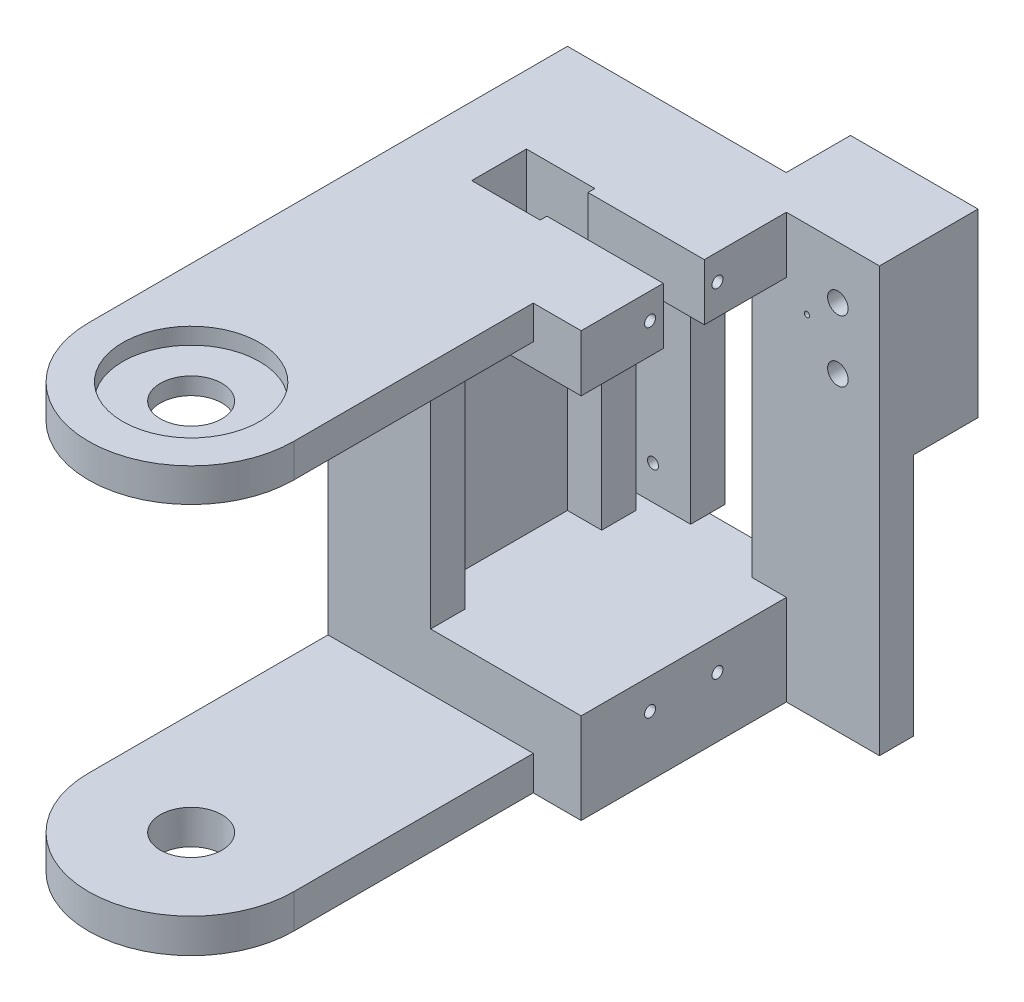
SolidWorks part; units mm, degrees
other "Marquage1"
sketch "Esquisse9" plane through (30.25, -27, 30) normal (0.9363, -0.2766, 0.2166) x (0.221, -0.0157, -0.9752)
sketch "Esquisse35" plane through (11.75, 27, 30) normal (0.9363, -0.2766, 0.2166) x (0.221, -0.0157, -0.9752)
sketch "Esquisse43" plane through (11.75, 27, 30) normal (0.9363, -0.2766, 0.2166) x (0.221, -0.0157, -0.9752)
sketch "Esquisse62" plane through (26.35, 27, 80) normal (0.9363, -0.2766, 0.2166) x (0.221, -0.0157, -0.9752)
ref_plane "Plan de face" through (0, 0, 0) normal (0, 0, 1) x (1, 0, 0)
ref_plane "Plan de dessus" through (0, 0, 0) normal (0, 1, 0) x (1, 0, 0)
ref_plane "Plan de droite" through (0, 0, 0) normal (1, 0, 0) x (0, 0, -1)
sketch "Esquisse1" plane through (0, 0, 0) normal (0, 0, 1) x (1, 0, 0)
  line L1 (-30.25, 32) -> (30.25, 32)
  line L2 (-30.25, 32) -> (-30.25, -32)
  line L3 (-30.25, -32) -> (30.25, -32)
  line L4 (30.25, 32) -> (30.25, -32)
  line L5 (-30.25, 32) -> (30.25, -32) construction
  line L6 (-30.25, -32) -> (30.25, 32) construction
  point P0 (0, 0)
  dimension "D1" = 60.5
  dimension "D2" = 64
extrude "Boss.-Extru.1" add sketch "Esquisse1" along normal blind 30
sketch "Esquisse2" plane through (30.25, 0, 0) normal (1, 0, 0) x (0, 0, -1)
  line L0 (-15, 32) -> (-15, -32) construction
  line L1 (-30, 32) -> (0, 32) construction
  line L2 (-30, -32) -> (0, -32) construction
  circle A0 centre (-15, -17) radius 4.5
  point P8 (-15, -17)
  dimension "D1" = 15
  dimension "D2" = 9
extrude "Enlèv. mat.-Extru.1" cut sketch "Esquisse2" against normal blind 32
sketch "Esquisse4" plane through (0, 0, 30) normal (0, 0, 1) x (1, 0, 0)
  line L0 (0, 0) -> (0, -11.7818) construction
  line L1 (-25.55, -56.5577) -> (25.55, -56.5577)
  line L2 (-25.55, -56.5577) -> (-25.55, 27)
  line L3 (-25.55, 27) -> (25.55, 27)
  line L4 (25.55, -56.5577) -> (25.55, 27)
  line L5 (30.25, 32) -> (-30.25, 32) construction
  dimension "D1" = 51.1
  dimension "D2" = 5
extrude "Enlèv. mat.-Extru.2" cut sketch "Esquisse4" against normal up to surface (30 mm away) up to face at (0, 0, 0)
sketch "Esquisse5" plane through (30.25, 0, 0) normal (1, 0, 0) x (0, 0, -1)
  circle A0 centre (-15, -17) radius 10.5
  dimension "D1" = 21
extrude "Enlèv. mat.-Extru.3" cut sketch "Esquisse5" against normal blind 2
sketch "Esquisse6" plane through (-25.55, 0, 0) normal (1, 0, 0) x (0, 0, -1)
  circle A0 centre (-15, -17) radius 10
extrude "Enlèv. mat.-Extru.4" cut sketch "Esquisse6" against normal up to surface (4.7 mm away) up to face at (-30.25, 0, 15)
sketch "Esquisse7" plane through (0, 0, 30) normal (0, 0, 1) x (1, 0, 0)
  line L0 (0, 0) -> (0, 32.5445) construction
  line L2 (-30.25, 32) -> (16.75, 32)
  line L3 (-30.25, 32) -> (-30.25, 89)
  line L4 (-30.25, 89) -> (16.75, 89)
  line L5 (16.75, 32) -> (16.75, 89)
  dimension "D1" = 57
  dimension "D2" = 47
extrude "Boss.-Extru.2" add sketch "Esquisse7" against normal up to surface (30 mm away) up to face at (0, -1.25, 0)
sketch "Esquisse8" plane through (0, 0, 30) normal (0, 0, 1) x (1, 0, 0)
  line L0 (-15.25, 90.392) -> (-15.25, 19.4965) construction
  line L1 (-30.25, 89) -> (-30.25, -32) construction
  line L2 (16.75, 60.5) -> (-55.9253, 60.5) construction
  line L3 (16.75, 32) -> (16.75, 89) construction
  line L4 (30.25, 32) -> (16.75, 32) construction
  line L6 (-15.25, 80.75) -> (11.75, 80.75)
  line L7 (-15.25, 80.75) -> (-15.25, 40.25)
  line L8 (-15.25, 40.25) -> (11.75, 40.25)
  line L10 (11.75, 40.25) -> (11.75, 32)
  line L11 (11.75, 101.1498) -> (21.75, 101.1498)
  line L12 (11.75, 101.1498) -> (11.75, 80.75)
  line L13 (11.75, 32) -> (21.75, 32)
  line L14 (21.75, 101.1498) -> (21.75, 32)
  dimension "D1" = 15
  dimension "D2" = 28.5
  dimension "D3" = 28.5
  dimension "D4" = 40.5
  dimension "D5" = 27
  dimension "D6" = 10
extrude "Enlèv. mat.-Extru.5" cut sketch "Esquisse8" against normal up to surface (30 mm away) up to face at (3.35, 16.8, 0)
sketch "Esquisse10" plane through (0, 80.75, 0) normal (0, -1, 0) x (1, 0, 0)
  line L0 (-1.75, 30) -> (-1.75, -1.0034) construction
  line L1 (-15.25, 15) -> (11.75, 15) construction
  line L2 (5.75, 0) -> (11.75, 0) construction
  line L4 (-15.25, 0) -> (11.75, 0)
  line L5 (11.75, 0) -> (11.75, 30)
  line L6 (11.75, 30) -> (-15.25, 30)
  line L7 (-15.25, 30) -> (-15.25, 0)
  line L8 (-15.25, 0) -> (-9.25, 0) construction
  line L9 (11.75, 0) -> (11.75, 30) construction
  line L10 (11.75, 30) -> (-15.25, 30) construction
  line L11 (-15.25, 30) -> (-15.25, 0) construction
  line L15 (-5.25, 11) -> (-5.25, 12)
  line L16 (-15.25, 19) -> (-5.25, 19)
  line L17 (-15.25, 19) -> (-15.25, 11)
  line L18 (-15.25, 11) -> (-5.25, 11)
  line L19 (34.75, 18) -> (34.75, 12)
  line L21 (-5.25, 19) -> (-5.25, 18)
  line L22 (-5.25, 18) -> (34.75, 18)
  line L24 (-5.25, 12) -> (34.75, 12)
  dimension "D2" = 6
  dimension "D4" = 10
  dimension "D1" = 0
extrude "Enlèv. mat.-Extru.6" cut sketch "Esquisse10" against normal up to surface (8.25 mm away) contours L17 L18 L15 L24 L19 L22 L21 L16 up to face at (-9.25, 89, 15)
sketch "Esquisse11" plane through (-15.25, 0, 0) normal (1, 0, 0) x (0, 0, -1)
  line L0 (-15, 103.0984) -> (-15, 64.9016) construction
  line L2 (0, 40.25) -> (-30, 40.25) construction
  line L3 (-30, 80.75) -> (-25, 80.75)
  line L4 (-30, 80.75) -> (-30, 40.25)
  line L5 (-30, 40.25) -> (-25, 40.25)
  line L6 (-25, 80.75) -> (-25, 40.25)
  line L7 (0, 40.25) -> (-5, 40.25)
  line L8 (-5, 80.75) -> (-5, 40.25)
  line L9 (0, 80.75) -> (-5, 80.75)
  line L10 (0, 80.75) -> (0, 40.25)
  point P3 (-15, 84)
  dimension "D1" = 5
extrude "Boss.-Extru.3" add sketch "Esquisse11" along normal blind 5
sketch "Esquisse12" plane through (11.75, 0, 0) normal (1, 0, 0) x (0, 0, -1)
  line L0 (-15, 89) -> (-15, 40.25) construction
  line L1 (-19, 89) -> (-11, 89) construction
  line L2 (0, 40.25) -> (-30, 40.25) construction
  line L3 (0, 80.75) -> (-12, 80.75) construction
  line L4 (-25, 60.5) -> (3.7732, 60.5) construction
  line L5 (-25, 40.25) -> (-25, 80.75) construction
  circle A0 centre (-19.925, 85.21) radius 0.5
  circle A1 centre (-10.075, 85.21) radius 0.5
  circle A2 centre (-10.075, 35.79) radius 0.5
  circle A3 centre (-19.925, 35.79) radius 0.5
  point P6 (-10.075, 85.21)
  point P9 (-19.925, 35.79)
  point P10 (-19.925, 85.21)
  point P15 (-10.075, 35.79)
  dimension "D3" = 1
  dimension "D1" = 4.46
  dimension "D2" = 4.925
  dimension "D4" = 4.925
  dimension "D5" = 4.46
extrude "Enlèv. mat.-Extru.7" cut sketch "Esquisse12" against normal blind 15
hole_wizard "Trou taraudé M2x0.42" positions "Esquisse3D2" profile "Esquisse14" tap size "M2x0.4" standard "Ansi Metric"
sketch3d "Esquisse3D2"
  line L0 (-3.25, 85.21, 19.925) -> (11.75, 85.21, 19.925) construction
  line L1 (-3.25, 85.21, 10.075) -> (11.75, 85.21, 10.075) construction
  line L2 (-3.25, 35.79, 10.075) -> (11.75, 35.79, 10.075) construction
  line L3 (-3.25, 35.79, 19.925) -> (11.75, 35.79, 19.925) construction
  point P0 (11.75, 85.21, 19.925)
  point P4 (11.75, 85.21, 10.075)
  point P8 (11.75, 35.79, 10.075)
  point P12 (11.75, 35.79, 19.925)
cosmetic thread "Filetage de perçage5" parameters "D1"=15, "D2"=2
cosmetic thread "Filetage de perçage6" parameters "D1"=15, "D2"=2
cosmetic thread "Filetage de perçage7" parameters "D1"=15, "D2"=2
cosmetic thread "Filetage de perçage8" parameters "D1"=15, "D2"=2
sketch "Esquisse14" plane through (11.75, 85.21, 19.925) normal (0, 1, 0) x (0, 0, -1)
  line L0 (0, 0) -> (0, 17.4807)
  line L1 (0, 17.4807) -> (0.8, 17)
  line L2 (0.8, 17) -> (0.8, 0)
  line L5 (0.8, 0) -> (0, 0)
  line L10 (0, 17.4807) -> (-0.8, 17) construction
  line L11 (0, -6.35) -> (0, 107.95) construction
  dimension "Diamètre du trou pour taraudage" = 1.6
  dimension "Profondeur du trou pour taraudage" = 17
  dimension "Angle de pointe" = 118
sketch "Esquisse15" plane through (-30.25, 0, 0) normal (-1, 0, 0) x (0, 0, 1)
  line L0 (30, -32) -> (0, -32) construction
  line L1 (40, -17) -> (30, -17)
  line L2 (0, -17) -> (-10, -17)
  arc A0 (5, -17) -> (25, -17) centre (15, -17) ccw construction
  arc A1 (0, -17) -> (30, -17) centre (15, -17) ccw
  arc A2 (-10, -17) -> (40, -17) centre (15, -17) ccw
  dimension "D1" = 20
  dimension "D2" = 50
extrude "Enlèv. mat.-Extru.8" cut sketch "Esquisse15" against normal up to surface (60.5 mm away) up to face at (30.25, -6.5, 15)
sketch "Esquisse17" plane through (-15.25, 0, 0) normal (1, 0, 0) x (0, 0, -1)
  line L0 (-15, 89) -> (-15, 40.25) construction
  line L1 (-19, 89) -> (-11, 89) construction
  line L2 (0, 40.25) -> (-30, 40.25) construction
  line L3 (-5, 70.15) -> (-34.9076, 70.15) construction
  line L4 (-5, 80.75) -> (-5, 40.25) construction
  line L5 (-25, 40.25) -> (-25, 80.75) construction
  line L6 (-5, 40.25) -> (-25, 40.25) construction
  circle A0 centre (-15, 70.15) radius 9.25
  point P14 (-15, 70.15)
  dimension "D1" = 10
  dimension "D2" = 29.9
sketch "Esquisse21" plane through (-30.25, 0, 0) normal (-1, 0, 0) x (0, 0, 1)
  circle A0 centre (15, 70.15) radius 9.25 construction
  circle A1 centre (15, 70.15) radius 9.25 construction
  circle A2 centre (15, 70.15) radius 1
  point P4 (15, 70.15)
sketch "Esquisse22" plane through (0, 0, 30) normal (0, 0, 1) x (1, 0, 0)
  line L0 (25.55, 27) -> (-25.55, 27) construction
  line L1 (39.5686, -40.8758) -> (-43.4034, -40.8758)
  line L2 (39.5686, -40.8758) -> (39.5686, 27)
  line L3 (39.5686, 27) -> (-43.4034, 27)
  line L4 (-43.4034, -40.8758) -> (-43.4034, 27)
extrude "Enlèv. mat.-Extru.10" cut sketch "Esquisse22" against normal up to surface (30 mm away) up to face at (1.8929, 33.5714, 0)
sketch "Esquisse23" plane through (0, 0, 0) normal (0, 0, -1) x (-1, 0, 0)
  line L0 (30.25, 58) -> (46.9038, 58) construction
  line L1 (30.25, 89) -> (30.25, 27) construction
  line L2 (30.25, 32) -> (85.25, 32)
  line L3 (30.25, 89) -> (85.25, 89)
  line L4 (30.25, 89) -> (30.25, 84.1)
  line L5 (30.25, 84.1) -> (85.25, 84.1)
  line L6 (85.25, 89) -> (85.25, 84.1)
  line L7 (85.25, 27) -> (85.25, 32)
  line L8 (30.25, 27) -> (85.25, 27)
  line L9 (30.25, 27) -> (30.25, 32)
  line L10 (30.25, 27) -> (-30.25, 27) construction
  dimension "D1" = 4.9
  dimension "D2" = 55
  dimension "D3" = 5
  dimension "D4" = 52.1
extrude "Boss.-Extru.4" add sketch "Esquisse23" against normal up to surface (30 mm away) up to face at (2.65, 53.8, 30)
sketch "Esquisse24" plane through (0, 27, 0) normal (0, -1, 0) x (1, 0, 0)
  line L0 (-85.25, 15) -> (-94.2291, 15) construction
  line L2 (-74.25, 35) -> (-74.25, -10.9716) construction
  line L3 (-30.25, 30) -> (-30.25, 0) construction
  line L4 (-30.25, 30) -> (-30.25, 0)
  circle A0 centre (-74.25, 15) radius 10
  dimension "D1" = 20
  dimension "D2" = 44
extrude "Enlèv. mat.-Extru.11" cut sketch "Esquisse24" against normal up to surface (62 mm away) contours A0
sketch "Esquisse25" plane through (0, 27, 0) normal (0, -1, 0) x (1, 0, 0)
  line L0 (30.25, 30) -> (-85.25, 30) construction
  line L1 (-85.25, 0) -> (30.25, 0) construction
  line L2 (-74.25, 44.1348) -> (-74.25, 30)
  line L3 (-74.25, 0) -> (-74.25, -14.1348)
  arc A0 (-74.25, 30) -> (-74.25, 0) centre (-74.25, 15) ccw
  arc A1 (-74.25, 44.1348) -> (-74.25, -14.1348) centre (-74.25, 15) ccw
extrude "Enlèv. mat.-Extru.12" cut sketch "Esquisse25" against normal up to surface (62 mm away) up to face at (-74.25, 89, 25)
sketch "Esquisse26" plane through (0, 27, 0) normal (0, -1, 0) x (1, 0, 0)
  circle A0 centre (-74.25, 15) radius 4.5
  circle A1 centre (-74.25, 15) radius 10.5
extrude "Boss.-Extru.5" add sketch "Esquisse26" against normal up to surface (5 mm away) up to face at (-74.25, 32, 25)
sketch "Esquisse27" plane through (0, 27, 0) normal (0, -1, 0) x (1, 0, 0)
  circle A0 centre (-74.25, 15) radius 10.5
extrude "Enlèv. mat.-Extru.13" cut sketch "Esquisse27" against normal offset from surface (2.5 mm away) 2.5 up to face at (-63.4171, 32, 15)
sketch "Esquisse28" plane through (0, 32, 0) normal (0, 1, 0) x (1, 0, 0)
  line L1 (11.75, 0) -> (33.2878, 0)
  line L2 (11.75, 0) -> (11.75, -33.2244)
  line L3 (11.75, -33.2244) -> (33.2878, -33.2244)
  line L4 (33.2878, 0) -> (33.2878, -33.2244)
extrude "Enlèv. mat.-Extru.14" cut sketch "Esquisse28" against normal up to surface (5 mm away) up to face at (-63.75, 27, 15)
sketch "Esquisse29" plane through (0, 0, 0) normal (0, 0, -1) x (-1, 0, 0)
  line L0 (74.25, 32) -> (30.25, 32) construction
  line L1 (30.25, 84.1) -> (25.25, 84.1)
  line L2 (30.25, 84.1) -> (30.25, 32)
  line L3 (30.25, 32) -> (25.25, 32)
  line L4 (25.25, 84.1) -> (25.25, 32)
  dimension "D1" = 5
extrude "Enlèv. mat.-Extru.15" cut sketch "Esquisse29" against normal up to surface (30 mm away) up to face at (-27.5833, 58.85, 30)
sketch "Esquisse31" plane through (0, 27, 0) normal (0, -1, 0) x (1, 0, 0)
  line L0 (-82.4117, 21.6059) -> (-85.25, 25.198)
  line L1 (-74.25, 4.5) -> (-85.25, 4.802)
  arc A0 (-85.25, 25.198) -> (-85.25, 4.802) centre (-74.25, 15) ccw
  arc A1 (-85.25, 4.802) -> (-74.25, 0) centre (-74.25, 15) ccw construction
  arc A2 (-82.4117, 21.6059) -> (-74.25, 4.5) centre (-74.25, 15) ccw
  circle A3 centre (-74.25, 15) radius 10.5 construction
  circle M1 centre (-74.25, 15) radius 10.5
  line M6 (-85.25, 25.198) -> (-85.25, 4.802)
extrude "Boss.-Extru.6" add sketch "Esquisse31" against normal up to surface (62 mm away) contours L1 L0 M1 M6 | A0 M6 up to face at (-74.25, 89, 25)
sketch "Esquisse32" plane through (0.0675, 0, 2.4599) normal (-0.0274, 0, -0.9996) x (-0.9996, 0, 0.0274)
  line L0 (85.3497, 32) -> (74.222, 32) construction
  line L1 (74.9218, 84.1) -> (113.711, 84.1)
  line L2 (74.9218, 84.1) -> (74.9218, 32)
  line L3 (74.9218, 32) -> (113.711, 32)
  line L4 (113.711, 84.1) -> (113.711, 32)
extrude "Enlèv. mat.-Extru.16" cut sketch "Esquisse32" against normal up to surface (24.429 mm away)
sketch "Esquisse33" plane through (0, 32, 0) normal (0, 1, 0) x (1, 0, 0)
  line L3 (-74.25, -30) -> (-25.25, -30)
  line L4 (-25.25, -30) -> (-25.25, 0)
  line L5 (-25.25, 0) -> (-74.25, 0)
  line L6 (-74.25, -30) -> (-25.25, -30)
  line L7 (-25.25, -30) -> (-25.25, 0)
  line L8 (-25.25, 0) -> (-74.25, 0)
  arc A1 (-74.25, 0) -> (-74.25, -30) centre (-74.25, -15) ccw
  arc A2 (-74.25, 0) -> (-74.25, -30) centre (-74.25, -15) ccw
  dimension "D1" = 0
extrude "Boss.-Extru.7" [suppressed] add sketch "Esquisse33" along normal blind 0.4
sketch "Esquisse34" [suppressed] plane through (0, 32, 0) normal (0, -1, 0) x (1, 0, 0)
  circle A0 centre (-74.25, 15) radius 4.5
extrude "Enlèv. mat.-Extru.17" [suppressed] cut sketch "Esquisse34" against normal up to surface (0.4 mm away)
sketch "Esquisse36" plane through (0, 27, 0) normal (0, -1, 0) x (1, 0, 0)
  line L3 (-96.1298, 39.4832) -> (-25.25, 39.4832)
  line L4 (-96.1298, 39.4832) -> (-96.1298, -4.8162)
  line L5 (-96.1298, -4.8162) -> (-25.25, -4.8162)
  line L6 (-25.25, 39.4832) -> (-25.25, -4.8162)
extrude "Enlèv. mat.-Extru.20" cut sketch "Esquisse36" against normal up to surface (62 mm away) contours L4 L3 L6 L5 up to face at (-14, 89, 15)
sketch "Esquisse37" plane through (-25.25, 0, 0) normal (-1, 0, 0) x (0, 0, 1)
  line L0 (30, 89) -> (30, 27) construction
  line L1 (0, 89) -> (30, 89)
  line L2 (0, 89) -> (0, 84.1)
  line L3 (0, 84.1) -> (30, 84.1)
  line L4 (30, 89) -> (30, 84.1)
  line L6 (0, 27) -> (30, 27)
  line L7 (0, 27) -> (0, 32)
  line L8 (0, 32) -> (30, 32)
  line L9 (30, 27) -> (30, 32)
  dimension "D1" = 4.9
  dimension "D2" = 5
  dimension "D3" = 52.1
extrude "Boss.-Extru.8" add sketch "Esquisse37" along normal blind 50
sketch "Esquisse38" plane through (0, 27, 0) normal (0, -1, 0) x (1, 0, 0)
  line L0 (-75.25, 15) -> (-54.6175, 15) construction
  line L1 (-75.25, 0) -> (-75.25, 30) construction
  circle A0 centre (-59.8855, 15) radius 4.5
extrude "Enlèv. mat.-Extru.21" cut sketch "Esquisse38" against normal up to surface (62 mm away)
sketch "Esquisse39" plane through (0, 89, 0) normal (0, 1, 0) x (1, 0, 0)
  circle A0 centre (-59.8855, -15) radius 10
extrude "Enlèv. mat.-Extru.22" cut sketch "Esquisse39" against normal up to surface (4.9 mm away) up to face at (-64.3855, 84.1, 15)
sketch "Esquisse40" plane through (0, 27, 0) normal (0, -1, 0) x (1, 0, 0)
  circle A0 centre (-59.8855, 15) radius 10.5
extrude "Enlèv. mat.-Extru.23" cut sketch "Esquisse40" against normal offset from surface (2.5 mm away) 2.5 up to face at (-55.3855, 32, 15)
sketch "Esquisse42" plane through (0, 27, 0) normal (0, -1, 0) x (1, 0, 0)
  line L0 (11.75, 30) -> (-75.25, 30) construction
  line L1 (-75.25, 0) -> (11.75, 0) construction
  line L2 (-59.8855, 38.9229) -> (-59.8855, 30)
  line L3 (-59.8855, 0) -> (-59.8855, -8.9229)
  arc A0 (-59.8855, 30) -> (-59.8855, 0) centre (-59.8855, 15) ccw
  arc A1 (-59.8855, 38.9229) -> (-59.8855, -8.9229) centre (-59.8855, 15) ccw
extrude "Enlèv. mat.-Extru.24" cut sketch "Esquisse42" against normal up to surface (62 mm away) up to face at (-59.8855, 89, 25)
sketch "Esquisse44" plane through (0, 0, 30) normal (0, 0, 1) x (1, 0, 0)
  line L0 (11.75, 89) -> (-59.8855, 89) construction
  line L1 (-25.25, 89) -> (4.75, 89)
  line L2 (-25.25, 89) -> (-25.25, 84.1)
  line L3 (-25.25, 84.1) -> (4.75, 84.1)
  line L4 (4.75, 89) -> (4.75, 84.1)
  line L5 (11.75, 27) -> (-59.8855, 27) construction
  line L6 (-25.25, 27) -> (4.75, 27)
  line L7 (-25.25, 27) -> (-25.25, 32)
  line L8 (-25.25, 32) -> (4.75, 32)
  line L9 (4.75, 27) -> (4.75, 32)
  dimension "D1" = 30
  dimension "D2" = 4.9
  dimension "D3" = 30
  dimension "D4" = 5
extrude "Boss.-Extru.9" add sketch "Esquisse44" along normal blind 50
sketch "Esquisse45" plane through (0, 89, 0) normal (0, 1, 0) x (1, 0, 0)
  line L0 (-10.25, -80) -> (-10.25, -26.0846) construction
  line L1 (4.75, -80) -> (-25.25, -80) construction
  line L2 (-25.25, -30) -> (-59.8855, -30) construction
  line L3 (-25.25, -80) -> (-25.25, -30) construction
  line L4 (4.75, -80) -> (4.75, -30) construction
  line L5 (-25.25, -65) -> (-36.2062, -65)
  line L6 (4.75, -65) -> (15.7062, -65)
  circle A0 centre (-10.25, -65) radius 4.5
  circle A1 centre (-10.25, -65) radius 10.5 construction
  arc A2 (-25.25, -65) -> (4.75, -65) centre (-10.25, -65) ccw
  arc A3 (-36.2062, -65) -> (15.7062, -65) centre (-10.25, -65) ccw
  dimension "D1" = 9
  dimension "D2" = 35
extrude "Enlèv. mat.-Extru.25" cut sketch "Esquisse45" against normal up to surface (62 mm away) up to face at (-49.3855, 27, 15)
sketch "Esquisse46" plane through (0, 89, 0) normal (0, 1, 0) x (1, 0, 0)
  circle A0 centre (-10.25, -65) radius 10
extrude "Enlèv. mat.-Extru.26" cut sketch "Esquisse46" against normal up to surface (4.9 mm away) up to face at (-10.25, 84.1, 69.5)
sketch "Esquisse47" plane through (0, 27, 0) normal (0, -1, 0) x (1, 0, 0)
  circle A0 centre (-10.25, 65) radius 10.5
extrude "Enlèv. mat.-Extru.27" cut sketch "Esquisse47" against normal offset from surface (2.5 mm away) 2.5 up to face at (-10.25, 32, 60.5)
sketch "Esquisse48" plane through (0, 89, 0) normal (0, 1, 0) x (1, 0, 0)
  line L0 (-25.25, 15) -> (-25.25, -37.5888)
  line L1 (-103.2246, 15) -> (-25.25, 15)
  line L2 (-103.2246, 15) -> (-103.2246, -30)
  line L5 (-25.25, -65) -> (-25.25, -30) construction
  line L6 (-25.25, -37.5888) -> (-103.2246, -37.5888)
  line L7 (-103.2246, -37.5888) -> (-103.2246, -30)
  dimension "D1" = 45
extrude "Enlèv. mat.-Extru.28" cut sketch "Esquisse48" against normal up to surface (62 mm away) up to face at (0.25, 27, 65)
sketch "Esquisse49" plane through (0, 0, 0) normal (0, 0, -1) x (-1, 0, 0)
  line L0 (25.25, 58) -> (-1.444, 58) construction
  line L1 (25.25, 89) -> (25.25, 27) construction
  line L3 (25.25, 73.5) -> (2.25, 73.5)
  line L4 (25.25, 73.5) -> (25.25, 42.5)
  line L5 (25.25, 42.5) -> (2.25, 42.5)
  line L6 (2.25, 73.5) -> (2.25, 42.5)
  dimension "D1" = 31
  dimension "D2" = 23
extrude "Boss.-Extru.10" add sketch "Esquisse49" along normal blind 5
sketch "Esquisse50" plane through (0, 0, -5) normal (0, 0, -1) x (-1, 0, 0)
  line L0 (25.25, 58) -> (-14.94, 58) construction
  line L1 (25.25, 42.5) -> (25.25, 73.5) construction
  line L2 (14, 58) -> (14, 55.6421) construction
  line L3 (20.25, 68.5) -> (7.75, 68.5) construction
  line L4 (20.25, 68.5) -> (20.25, 47.5) construction
  line L5 (20.25, 47.5) -> (7.75, 47.5) construction
  line L6 (7.75, 68.5) -> (7.75, 47.5) construction
  circle A0 centre (7.75, 68.5) radius 0.45
  circle A1 centre (7.75, 47.5) radius 0.45
  circle A2 centre (20.25, 68.5) radius 0.45
  circle A3 centre (20.25, 47.5) radius 0.45
  dimension "D3" = 0.9
  dimension "D1" = 12.5
  dimension "D2" = 21
  dimension "D4" = 5
extrude "Enlèv. mat.-Extru.29" cut sketch "Esquisse50" against normal up to surface (5 mm away) up to face at (-6.25, 58, 0)
hole_wizard "Trou taraudé M2x0.43" positions "Esquisse3D3" profile "Esquisse51" tap size "M2x0.4" standard "Ansi Metric"
sketch3d "Esquisse3D3"
  line L0 (-7.75, 47.5, 0) -> (-7.75, 47.5, -5) construction
  line L1 (-7.75, 68.5, 0) -> (-7.75, 68.5, -5) construction
  line L2 (-20.25, 68.5, 0) -> (-20.25, 68.5, -5) construction
  line L3 (-20.25, 47.5, 0) -> (-20.25, 47.5, -5) construction
  point P5 (-7.75, 47.5, -5)
  point P9 (-7.75, 68.5, -5)
  point P13 (-20.25, 68.5, -5)
  point P17 (-20.25, 47.5, -5)
sketch "Esquisse51" plane through (-7.75, 47.5, -5) normal (1, 0, 0) x (0, 1, 0)
  line L0 (0, 0) -> (0, 10.4807)
  line L1 (0, 10.4807) -> (0.8, 10)
  line L2 (0.8, 10) -> (0.8, 0)
  line L5 (0.8, 0) -> (0, 0)
  line L10 (0, 10.4807) -> (-0.8, 10) construction
  line L11 (0, -6.35) -> (0, 107.95) construction
  dimension "Diamètre du trou pour taraudage" = 1.6
  dimension "Profondeur du trou pour taraudage" = 10
  dimension "Angle de pointe" = 118
cosmetic thread "Filetage de perçage9" parameters "D1"=130, "D2"=2
cosmetic thread "Filetage de perçage10" parameters "D1"=130, "D2"=2
cosmetic thread "Filetage de perçage11" parameters "D1"=130, "D2"=2
cosmetic thread "Filetage de perçage12" parameters "D1"=130, "D2"=2
sketch "Esquisse52" plane through (0, 0, 0) normal (0, 0, -1) x (-1, 0, 0)
  line L0 (25.25, 27) -> (-11.75, 27) construction
  line L1 (-11.75, 89) -> (-26.75, 89)
  line L3 (-6.7144, 27) -> (-26.75, 27)
  line L4 (-26.75, 89) -> (-26.75, 27)
  line L5 (-11.75, 40.25) -> (10.25, 40.25) construction
  line L6 (-11.75, 89) -> (-6.7144, 89)
  line L9 (-6.7144, 80.75) -> (-6.7144, 40.25)
  line L11 (-6.7144, 40.25) -> (25.25, 40.25)
  line L12 (25.25, 42.5) -> (25.25, 27) construction
  line L13 (25.25, 40.25) -> (25.25, 27)
  line L14 (25.25, 27) -> (-6.7144, 27)
  line L15 (25.25, 89) -> (-6.7144, 89)
  line L16 (-6.7144, 80.75) -> (25.25, 80.75)
  line L17 (10.25, 80.75) -> (-11.75, 80.75) construction
  line L18 (25.25, 89) -> (25.25, 73.5) construction
  line L19 (25.25, 89) -> (25.25, 80.75)
  dimension "D1" = 15
extrude "Boss.-Extru.11" add sketch "Esquisse52" along normal blind 5 separate body
sketch "Esquisse53" plane through (0, 27, 0) normal (0, -1, 0) x (1, 0, 0)
  circle A0 centre (-10.25, 65) radius 10.5
  circle A1 centre (-10.25, 65) radius 4.5
extrude "Boss.-Extru.12" add sketch "Esquisse53" against normal up to surface (2.5 mm away) up to face at (-10.25, 29.5, 54.5)
sketch "Esquisse55" plane through (0, 84.1, 0) normal (0, -1, 0) x (1, 0, 0)
  circle A0 centre (-10.25, 65) radius 10 construction
  circle A1 centre (-10.25, 65) radius 10
  circle A2 centre (-10.25, 65) radius 4.5
extrude "Boss.-Extru.14" add sketch "Esquisse55" against normal blind 2.5
sketch "Esquisse56" plane through (0, 0, -5) normal (0, 0, -1) x (-1, 0, 0)
  line L1 (-26.75, 89) -> (-26.75, 27) construction
  line L2 (-19.27, 89) -> (-19.27, 81.292) construction
  line L3 (25.25, 89) -> (-26.75, 89) construction
  line L5 (-19.27, 81.292) -> (-19.27, 63.426) construction
  circle A0 centre (-14.75, 77.552) radius 0.3
  circle A1 centre (-19.27, 81.292) radius 1.5
  circle A2 centre (-19.27, 72.292) radius 1.5
  dimension "D4" = 3
  dimension "D5" = 3
  dimension "D1" = 12
  dimension "D2" = 7.708
  dimension "D3" = 9
  dimension "D6" = 3.74
extrude "Enlèv. mat.-Extru.30" cut sketch "Esquisse56" against normal up to surface (5 mm away) up to face at (-4.2589, 59.25, 0)
sketch "Esquisse58" plane through (26.75, 0, 0) normal (1, 0, 0) x (0, 0, -1)
  line L1 (-3.5657, 91.4742) -> (9.5479, 91.4742)
  line L2 (-3.5657, 91.4742) -> (-3.5657, 25.4461)
  line L3 (-3.5657, 25.4461) -> (9.5479, 25.4461)
  line L4 (9.5479, 91.4742) -> (9.5479, 25.4461)
extrude "Enlèv. mat.-Extru.31" cut sketch "Esquisse58" against normal blind 0.4
sketch "Esquisse59" plane through (0, 0, -5) normal (0, 0, -1) x (-1, 0, 0)
  line L0 (-6.7144, 40.25) -> (-6.7144, 80.75) construction
  line L1 (-26.35, 89) -> (-6.7144, 89)
  line L2 (-26.35, 89) -> (-26.35, 62.5886)
  line L3 (-26.35, 62.5886) -> (-6.7144, 62.5886)
  line L4 (-6.7144, 89) -> (-6.7144, 62.5886)
  circle A0 centre (-14.75, 77.552) radius 0.3 construction
  circle A1 centre (-19.27, 72.292) radius 1.5 construction
  circle A2 centre (-19.27, 81.292) radius 1.5 construction
  circle A3 centre (-14.75, 77.552) radius 0.3
  circle A4 centre (-19.27, 72.292) radius 1.5
  circle A5 centre (-19.27, 81.292) radius 1.5
extrude "Boss.-Extru.15" add sketch "Esquisse59" along normal blind 9.4
hole_wizard "Trou taraudé M1.4x0.31" positions "Esquisse3D5" profile "Esquisse61" tap size "M1.4x0.3" standard "Ansi Metric"
sketch3d "Esquisse3D5"
  line L0 (14.75, 77.552, 0) -> (14.75, 77.552, -14.4) construction
  point P0 (14.75, 77.552, -14.4)
sketch "Esquisse61" plane through (14.75, 77.552, -14.4) normal (1, 0, 0) x (0, 1, 0)
  line L0 (0, 0) -> (0, 14.6305)
  line L1 (0, 14.6305) -> (0.55, 14.3)
  line L2 (0.55, 14.3) -> (0.55, 0)
  line L5 (0.55, 0) -> (0, 0)
  line L10 (0, 14.6305) -> (-0.55, 14.3) construction
  line L11 (0, -6.35) -> (0, 107.95) construction
  dimension "Diamètre du trou pour taraudage" = 1.1
  dimension "Profondeur du trou pour taraudage" = 14.3
  dimension "Angle de pointe" = 118
cosmetic thread "Filetage de perçage13" parameters "D1"=12.8, "D2"=1.4
sketch "Esquisse63" plane through (26.35, 0, 0) normal (1, 0, 0) x (0, 0, -1)
  line L1 (-1.5006, 93.3875) -> (15.7461, 93.3875)
  line L2 (-1.5006, 93.3875) -> (-1.5006, 23.1235)
  line L3 (-1.5006, 23.1235) -> (15.7461, 23.1235)
  line L4 (15.7461, 93.3875) -> (15.7461, 23.1235)
extrude "Enlèv. mat.-Extru.32" cut sketch "Esquisse63" against normal blind 1
equation "\"D3@Esquisse50\"=0.9mm"
equation "\"D4@Esquisse56\"=\"D5@Esquisse56\""
